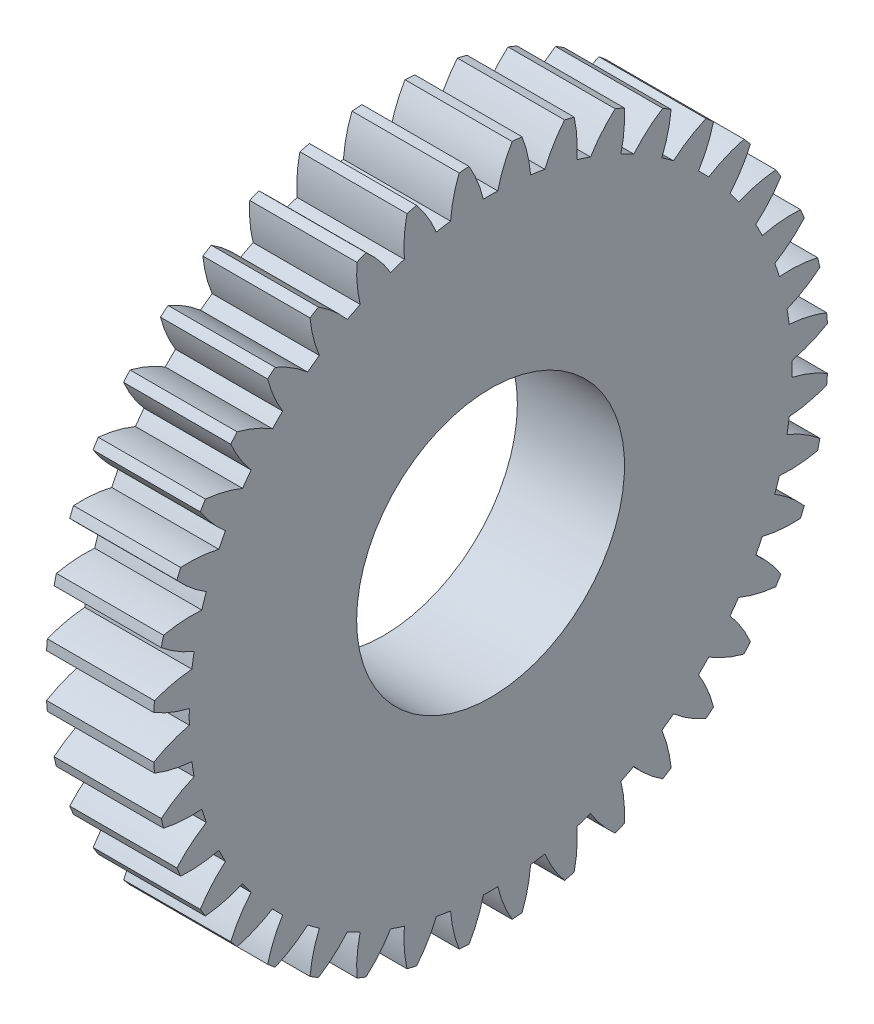
SolidWorks part; units mm, degrees
ref_plane "Plane1" through (0, 0, 0) normal (0, 0, 1) x (1, 0, 0)
ref_plane "Plane2" through (0, 0, 0) normal (0, 1, 0) x (1, 0, 0)
ref_plane "Plane3" through (0, 0, 0) normal (1, 0, 0) x (0, 0, -1)
sketch "HoldingSke" plane through (0, 0, 0) normal (0, 1, 0) x (1, 0, 0)
  line L0 (0, 0) -> (1.2767, -1.0713)
  line L1 (-15, 0) -> (100, 0) construction
  line L2 (0, 0) -> (-2.1039, 2.3779)
  line L3 (0, 0) -> (-11.863, 4.5341)
  line L4 (0, 0) -> (6.6156, 5.5511)
  line L5 (0, 0) -> (-46.8476, -17.4728)
  line L6 (0, 0) -> (-3.3159, -2.2372)
  line L7 (-2.1039, 2.3779) -> (8.6586, 51.2059)
  line L8 (-76.2, 54.61) -> (-74.4, 54.61)
  line L9 (-71.009, 38.7566) -> (-53.1078, 45.2721)
  line L10 (-76.2, 71.12) -> (104.1128, 71.12)
  line L11 (0, 0) -> (-4, 0)
  line L12 (-76.2, 101.6) -> (-76.177, 101.6)
  line L13 (24.9733, 27.94) -> (52.9518, 28.4284)
  line L14 (24.9733, 27.94) -> (24.9743, 27.94)
  line L15 (24.9733, 27.94) -> (100.4006, 29.5858)
  line L16 (-63.627, -0.6) -> (-12.827, -0.6)
  circle A0 centre (0, 0) radius 5
  circle A1 centre (0, 0) radius 11.249
  circle A2 centre (0, 0) radius 37.5
  circle A3 centre (0, 0) radius 5
  dimension "MHD" = 22.498
  dimension "Hub_dia" = 75
  dimension "Bore" = 10
  dimension "MBD" = 10
  dimension "Num_teeth" = 40
  dimension "Pitch" = 1.6667
  dimension "Overall_len" = 50
  dimension "Show_teeth" = 40
  dimension "Thickness" = 4
  dimension "OAL" = 50.0001
  dimension "T_dim" = 1.8
  dimension "Ap" = 20
  dimension "H" = 19.05
  dimension "Pitch_radius" = 180.3128
  dimension "Width" = 4
  dimension "Backlash" = 0.023
  dimension "Addendum_fac" = 1
  dimension "Dedendum_fac" = 1.25
  dimension "Clearance_fac" = 0.25
  dimension "Dedendum_add" = 0.001
  dimension "Module" = 0.6
sketch "BasProSke" plane through (0, 0, 0) normal (0, 1, 0) x (1, 0, 0)
  line L0 (-10, 0) -> (60, 0) construction
  line L1 (0, 0) -> (0, 12.6)
  line L2 (0, 0) -> (4, 0)
  line L3 (4, 0) -> (4, 12.6)
  line L4 (4, 12.6) -> (0, 12.6)
  dimension "Thickness" = 4
  dimension "Diameter" = 25.2
revolve "Base-Revolve" add sketch "BasProSke" angle 360 about L0
sketch "TooCutSke" plane through (0, 0, 0) normal (1, 0, 0) x (0, 0, -1)
  line L1 (0, 0) -> (0, 107) construction
  line L2 (0, 0) -> (-0.5114, 11.9891) construction
  line L3 (0, 0) -> (-1.8818, 23.9106) construction
  line L4 (-0.5114, 11.9891) -> (-0.9409, 11.9553) construction
  arc A0 (0.2694, 11.2458) -> (-0.2694, 11.2458) centre (0, 0) ccw
  arc A1 (0.8191, 12.5988) -> (-0.8191, 12.5988) centre (0, 0) ccw
  circle A2 centre (0, 0) radius 12 construction
  circle A3 centre (0, 0) radius 11.2763 construction
  arc A4 (-0.2694, 11.2458) -> (-0.8191, 12.5988) centre (-4.9396, 10.1368) ccw
  arc A5 (0.8191, 12.5988) -> (0.2694, 11.2458) centre (4.9396, 10.1368) ccw
  dimension "Root_dia" = 22.498
  dimension "Overcut_dia" = 25.2508
  dimension "Pitch_dia" = 24
  dimension "Base_dia" = 22.5526
  dimension "Flank_rad" = 4.8
  dimension "Half_ang" = 4.5
  dimension "Half_CT" = 0.4309
extrude "ToothCut" cut sketch "TooCutSke" along normal through all
fillet "Breaks" [suppressed] radius 0.012
fillet "RootFillets" [suppressed] radius 0.151
pattern_circular "TeethCuts" count 40 every 9 about axis through (-10, 0, 0) along (1, 0, 0) of "ToothCut", "RootFillets", "Breaks"
sketch "HubNeaOneSke" plane through (0, 0, 0) normal (-1, 0, 0) x (0, 0, 1)
  circle A0 centre (0, 0) radius 11.249
  dimension "Diameter" = 22.498
extrude "HubNearOne" [suppressed] add sketch "HubNeaOneSke" along normal blind 46.0001
sketch "HubNeaBotSke" plane through (0, 0, 0) normal (-1, 0, 0) x (0, 0, 1)
  circle A0 centre (0, 0) radius 11.249
  dimension "Diameter" = 22.498
extrude "HubNearBoth" [suppressed] add sketch "HubNeaBotSke" along normal blind 23
ref_plane "FarPln" through (4, 0, 0) normal (1, 0, 0) x (0, 0, -1)
sketch "HubFarSke" plane through (4, 0, 0) normal (1, 0, 0) x (0, 0, -1)
  circle A0 centre (0, 0) radius 11.249
  dimension "Diameter" = 22.498
extrude "HubFar" [suppressed] add sketch "HubFarSke" along normal blind 23
sketch "BorSke" plane through (0, 0, 0) normal (1, 0, 0) x (0, 0, -1)
  circle A0 centre (0, 0) radius 5
  dimension "Diameter" = 10
extrude "Bore" cut sketch "BorSke" along normal mid plane 100.0001
sketch "KeySke" plane through (0, 0, 0) normal (1, 0, 0) x (0, 0, -1)
  line L0 (-2, 0) -> (-2, 6.8)
  line L1 (-2, 6.8) -> (2, 6.8)
  line L2 (2, 6.8) -> (2, 0)
  line L3 (0, 0) -> (0, 34) construction
  line L4 (-2, 0) -> (2, 0)
  dimension "Width" = 4
  dimension "Offset" = 6.8
extrude "Keyway" [suppressed] cut sketch "KeySke" along normal mid plane 100.0001
pattern_circular "Keyway2" [suppressed] count 2 every 90 about axis through (-10, 0, 0) along (1, 0, 0)
equation "' \"Module@HoldingSke\" = 6.35"
equation "' \"Num_teeth@HoldingSke\" = 12"
equation "' \"Ap@HoldingSke\" =  20"
equation "' \"Ap@HoldingSke\" = 20"
equation "' \"Width@HoldingSke\" = 0.5 * 25.4"
equation "' \"Hub_dia@HoldingSke\"= 1 * 25.4"
equation "' \"Hub_dia@HoldingSke\" = 1 * 25.4"
equation "' \"Overall_len@HoldingSke\" = 1.0 * 25.4"
equation "' \"Bore@HoldingSke\" = 0.75 * 25.4"
equation "' \"T_dim@HoldingSke\" = 0.1 * 25.4"
equation "' \"Width@KeySke\" = 0.25 * 25.4"
equation "' \"Show_teeth@HoldingSke\" = 13"
equation "' \"Backlash@HoldingSke\" = 0.009 * 25.4"
equation "' \"Addendum_fac@HoldingSke\" = 1.0"
equation "' \"Dedendum_fac@HoldingSke\" = 1.25"
equation "' \"Dedendum_add@HoldingSke\" = 0.00005 * 25.4"
equation "' \"Clearance_fac@HoldingSke\" = 0.25"
equation "\"Pitch@HoldingSke\" = 1 / \"Module@HoldingSke\""
equation "\"Overcut_dia@TooCutSke\" = (\"Num_teeth@HoldingSke\" + 2 * \"Addendum_fac@HoldingSke\") / \"Pitch@HoldingSke\" + 0.002 * 25.4"
equation "\"Pitch_dia@TooCutSke\" = \"Num_teeth@HoldingSke\" / \"Pitch@HoldingSke\""
equation "\"Base_dia@TooCutSke\" = \"Num_teeth@HoldingSke\" / \"Pitch@HoldingSke\" * cos((\"Ap@HoldingSke\"  * 3.14159265 / 180))"
equation "\"Root_dia@TooCutSke\" = (\"Num_teeth@HoldingSke\" + 2) / \"Pitch@HoldingSke\" - 2 * (\"Addendum_fac@HoldingSke\" + \"Dedendum_fac@HoldingSke\") / \"Pitch@HoldingSke\" - \"Dedendum_add@HoldingSke\" * 2"
equation "\"Half_ang@TooCutSke\" = 180 / \"Num_teeth@HoldingSke\""
equation "\"Half_CT@TooCutSke\" = \"Num_teeth@HoldingSke\" / \"Pitch@HoldingSke\" * sin((3.14159265 / 2 / \"Num_teeth@HoldingSke\")) / 2 - 7 * \"Backlash@HoldingSke\" / 4"
equation "\"Flank_rad@TooCutSke\" = \"Num_teeth@HoldingSke\" / \"Pitch@HoldingSke\" / 5"
equation "\"Radius@RootFillets\" = \"Clearance_fac@HoldingSke\" / \"Pitch@HoldingSke\" + \"Dedendum_add@HoldingSke\""
equation "\"Break_rad@Breaks\" = 0.02 / \"Pitch@HoldingSke\""
equation "\"Thickness@HoldingSke\" = \"Width@HoldingSke\""
equation "\"OAL@HoldingSke\" = \"Thickness@HoldingSke\""
equation "\"MHD@HoldingSke\" = (\"Num_teeth@HoldingSke\" + 2) / \"Pitch@HoldingSke\" - 2 * (\"Addendum_fac@HoldingSke\" + \"Dedendum_fac@HoldingSke\")  / \"Pitch@HoldingSke\" - \"Dedendum_add@HoldingSke\" * 2"
equation "\"MBD@HoldingSke\" = (\"Num_teeth@HoldingSke\" + 2) / \"Pitch@HoldingSke\" - 2 * (\"Addendum_fac@HoldingSke\" + \"Dedendum_fac@HoldingSke\")  / \"Pitch@HoldingSke\" - \"Dedendum_add@HoldingSke\" * 2 - 0.002 * 25.4"
equation "\"MHD@HoldingSke\" = ((sgn( \"MHD@HoldingSke\" - \"Hub_dia@HoldingSke\" )-1)*( \"MHD@HoldingSke\" - \"Hub_dia@HoldingSke\" ))/-2+ \"Hub_dia@HoldingSke\""
equation "\"MBD@HoldingSke\" = ((sgn( \"MBD@HoldingSke\" - \"Bore@HoldingSke\" )-1)*( \"MBD@HoldingSke\" - \"Bore@HoldingSke\" ))/-2+ \"Bore@HoldingSke\""
equation "\"OAL@HoldingSke\" = ((sgn( \"OAL@HoldingSke\" - \"Overall_len@HoldingSke\" )+1)*( \"OAL@HoldingSke\" - \"Overall_len@HoldingSke\" ))/2 + \"Overall_len@HoldingSke\" + 0.000002 * 25.4"
equation "\"Num_teeth@TeethCuts\" = int( \"Show_teeth@HoldingSke\" ) + 1"
equation "\"Num_teeth@TeethCuts\" = ((sgn( \"Num_teeth@TeethCuts\" - \"Num_teeth@HoldingSke\" )-1)*( \"Num_teeth@TeethCuts\" - \"Num_teeth@HoldingSke\" ))/-2+ \"Num_teeth@HoldingSke\""
equation "\"Num_teeth@TeethCuts\" = ((sgn( \"Num_teeth@TeethCuts\" - 2.0)+1)*( \"Num_teeth@TeethCuts\" - 2.0))/2 +2.0"
equation "\"Angle@TeethCuts\" = 360.0 / \"Num_teeth@HoldingSke\""
equation "\"Diameter@BasProSke\" = (\"Num_teeth@HoldingSke\" + 2 * \"Addendum_fac@HoldingSke\") / \"Pitch@HoldingSke\""
equation "\"Thickness@BasProSke\"  = \"Thickness@HoldingSke\""
equation "' \"Fillet_rad@BasProSke\" =  \"Thickness@HoldingSke\" * 0.05"
equation "' \"Fillet_rad@BasProSke\" = \"Thickness@HoldingSke\" * 0.05"
equation "\"MHD@HoldingSke\" = ((sgn( \"MHD@HoldingSke\" - \"Root_dia@TooCutSke\" )-1)*( \"MHD@HoldingSke\" - \"Root_dia@TooCutSke\" ))/-2+ \"Root_dia@TooCutSke\""
equation "\"Diameter@HubNeaOneSke\" = \"MHD@HoldingSke\""
equation "\"Length@HubNearOne\" = \"OAL@HoldingSke\" - \"Thickness@BasProSke\""
equation "\"Diameter@HubNeaBotSke\" = \"MHD@HoldingSke\""
equation "\"Length@HubNearBoth\" = ( \"OAL@HoldingSke\" - \"Thickness@BasProSke\" ) / 2.0"
equation "\"Thickness@FarPln\" = \"Thickness@BasProSke\""
equation "\"Diameter@HubFarSke\" = \"MHD@HoldingSke\""
equation "\"Length@HubFar\" = ( \"OAL@HoldingSke\" - \"Thickness@BasProSke\" ) / 2.0"
equation "\"Diameter@BorSke\" = \"MBD@HoldingSke\""
equation "\"D1@Bore\" = \"OAL@HoldingSke\" * 2.0"
equation "\"D1@Keyway\" = \"OAL@HoldingSke\" * 2.0"
equation "\"Offset@KeySke\" = \"T_dim@HoldingSke\" + \"MBD@HoldingSke\" / 2.0"
